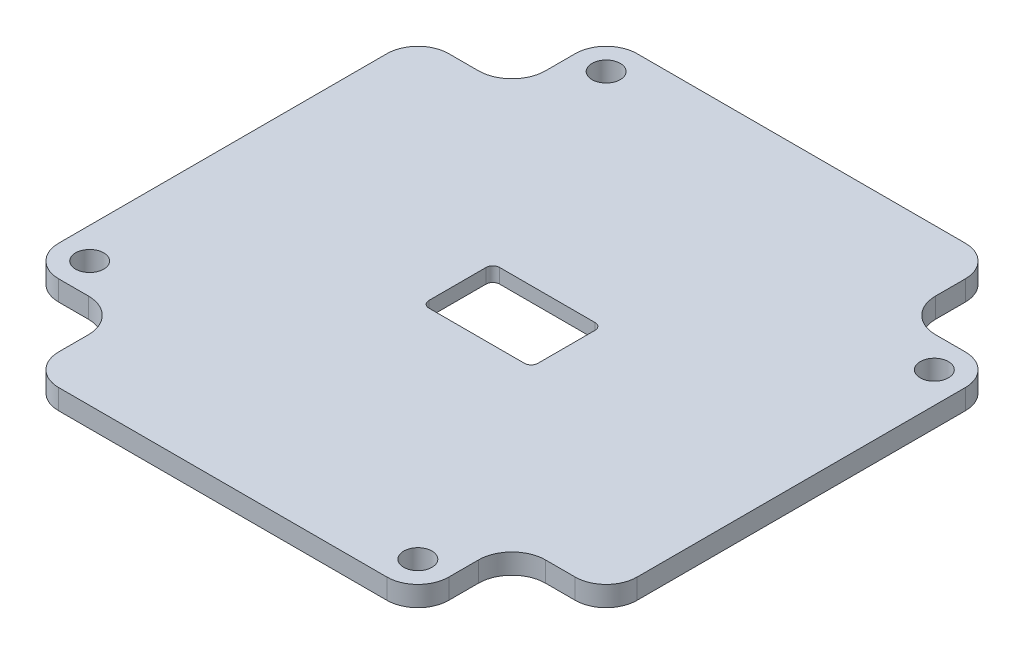
SolidWorks part; units mm, degrees
ref_plane "Front Plane" through (0, 0, 0) normal (0, 0, 1) x (1, 0, 0)
ref_plane "Top Plane" through (0, 0, 0) normal (0, 1, 0) x (1, 0, 0)
ref_plane "Right Plane" through (0, 0, 0) normal (1, 0, 0) x (0, 0, -1)
sketch "Sketch1" plane through (0, 0, 0) normal (0, 1, 0) x (1, 0, 0)
  line L1 (-43, -43) -> (43, -43)
  line L2 (-43, -43) -> (-43, 43)
  line L3 (-43, 43) -> (43, 43)
  line L4 (43, -43) -> (43, 43)
  line L5 (-43, -43) -> (43, 43) construction
  line L6 (-43, 43) -> (43, -43) construction
  point P0 (0, 0)
  dimension "D1" = 86
  dimension "D2" = 86
extrude "Boss-Extrude1" add sketch "Sketch1" along normal blind 3
sketch "Sketch2" plane through (0, 3, 0) normal (0, 1, 0) x (1, 0, 0)
  line L0 (29, 43) -> (29, 29)
  line L1 (-43, 43) -> (-29, 43)
  line L2 (-43, 43) -> (-43, 29)
  line L3 (-43, 29) -> (-29, 29)
  line L4 (-29, 43) -> (-29, 29)
  line L5 (29, 43) -> (43, 43)
  line L6 (43, 43) -> (43, 29)
  line L7 (29, 29) -> (43, 29)
  line L8 (29, -29) -> (29, -43)
  line L9 (29, -29) -> (43, -29)
  line L10 (43, -29) -> (43, -43)
  line L11 (29, -43) -> (43, -43)
  line L12 (-43, -29) -> (-43, -43)
  line L13 (-43, -29) -> (-29, -29)
  line L14 (-29, -29) -> (-29, -43)
  line L15 (-43, -43) -> (-29, -43)
  line L17 (-8.1, -5.25) -> (8.1, -5.25)
  line L18 (-8.1, -5.25) -> (-8.1, 5.25)
  line L19 (-8.1, 5.25) -> (8.1, 5.25)
  line L20 (8.1, -5.25) -> (8.1, 5.25)
  line L21 (-8.1, -5.25) -> (8.1, 5.25) construction
  line L22 (-8.1, 5.25) -> (8.1, -5.25) construction
  point P0 (0, 0)
  point P15 (0, 0)
  dimension "D1" = 16.2
  dimension "D2" = 14
  dimension "D3" = 14
  dimension "D6" = 10.5
  dimension "D4" = 2
  dimension "D5" = 2
extrude "Cut-Extrude1" cut sketch "Sketch2" against normal through all
fillet "Fillet1" radius 4.6 8 edges at (29, 1.5, 43) (-43, 1.5, -29) (-43, 1.5, 29) (-29, 1.5, 43) (43, 1.5, 29) (43, 1.5, -29) (29, 1.5, -43) (-29, 1.5, -43)
fillet "Fillet2" radius 5 4 edges at (29, 1.5, -29) (-29, 1.5, -29) (-29, 1.5, 29) (29, 1.5, 29)
sketch "Sketch3" plane through (0, 3, 0) normal (0, 1, 0) x (1, 0, 0)
  circle A1 centre (38.4, 24.4) radius 2.1
  circle A2 centre (-24.4, 38.4) radius 2.1
  circle A3 centre (24.4, -38.4) radius 2.1
  circle A4 centre (-38.4, -24.4) radius 2.1
  dimension "D1" = 4.2
  dimension "D2" = 4.2
  dimension "D3" = 4.2
  dimension "D4" = 4.2
extrude "Cut-Extrude2" cut sketch "Sketch3" against normal through all
sketch "Sketch4" plane through (0, 3, 0) normal (0, 1, 0) x (1, 0, 0)
  line L1 (11.75, -11.4) -> (-11.75, -11.4)
  line L2 (11.75, -11.4) -> (11.75, 11.4)
  line L3 (11.75, 11.4) -> (-11.75, 11.4)
  line L4 (-11.75, -11.4) -> (-11.75, 11.4)
  line L5 (11.75, -11.4) -> (-11.75, 11.4) construction
  line L6 (11.75, 11.4) -> (-11.75, -11.4) construction
  point P0 (0, 0)
  dimension "D1" = 23.5
  dimension "D2" = 22.8
extrude "Cut-Extrude3" cut sketch "Sketch4" along normal blind 0.85 from surface at -3 starting at face at (-24.4, 0, -36.3)
fillet "Fillet3" radius 3.4 4 edges at (-11.75, 0.425, 11.4) (11.75, 0.425, 11.4) (11.75, 0.425, -11.4) (-11.75, 0.425, -11.4)
sketch "Sketch5" plane through (0, 3, 0) normal (0, 1, 0) x (1, 0, 0)
  line L0 (11.75, -8) -> (11.75, 8) construction
  line L1 (-38, -11.4) -> (-16.75, -11.4)
  line L2 (-38, -11.4) -> (-38, 11.4)
  line L3 (-38, 11.4) -> (-16.75, 11.4)
  line L4 (-16.75, -11.4) -> (-16.75, 11.4)
  line L5 (-38, -11.4) -> (-16.75, 11.4) construction
  line L6 (-38, 11.4) -> (-16.75, -11.4) construction
  line L7 (-11.75, 16.4) -> (11.75, 16.4)
  line L8 (-11.75, 16.4) -> (-11.75, 38)
  line L9 (-11.75, 38) -> (11.75, 38)
  line L10 (11.75, 16.4) -> (11.75, 38)
  line L11 (-11.75, 16.4) -> (11.75, 38) construction
  line L12 (-11.75, 38) -> (11.75, 16.4) construction
  line L13 (16.75, -11.4) -> (38, -11.4)
  line L14 (16.75, -11.4) -> (16.75, 11.4)
  line L15 (16.75, 11.4) -> (38, 11.4)
  line L16 (38, -11.4) -> (38, 11.4)
  line L17 (16.75, -11.4) -> (38, 11.4) construction
  line L18 (16.75, 11.4) -> (38, -11.4) construction
  line L19 (-11.75, -16.4) -> (11.75, -16.4)
  line L20 (-11.75, -16.4) -> (-11.75, -38)
  line L21 (-11.75, -38) -> (11.75, -38)
  line L22 (11.75, -16.4) -> (11.75, -38)
  line L23 (-11.75, -16.4) -> (11.75, -38) construction
  line L24 (-11.75, -38) -> (11.75, -16.4) construction
  line L25 (8.35, 11.4) -> (-8.35, 11.4) construction
  line L26 (-43, 24.4) -> (-43, -24.4) construction
  line L27 (-11.75, 8) -> (-11.75, -8) construction
  line L28 (43, -24.4) -> (43, 24.4) construction
  line L29 (8.35, 11.4) -> (-8.35, 11.4) construction
  line L30 (24.4, 43) -> (-24.4, 43) construction
  line L31 (-8.35, -11.4) -> (8.35, -11.4) construction
  line L32 (-24.4, -43) -> (24.4, -43) construction
  line L33 (-24, 43) -> (-24, -43)
  line L34 (-38, 38) -> (-16.75, 38)
  line L35 (-38, 38) -> (-38, 16.4)
  line L36 (-38, 16.4) -> (-16.75, 16.4)
  line L37 (-16.75, 38) -> (-16.75, 16.4)
  line L38 (-38, 38) -> (-16.75, 16.4) construction
  line L39 (-38, 16.4) -> (-16.75, 38) construction
  line L40 (-38, -38) -> (-16.75, -38)
  line L41 (-38, -38) -> (-38, -16.4)
  line L42 (-38, -16.4) -> (-16.75, -16.4)
  line L43 (-16.75, -38) -> (-16.75, -16.4)
  line L44 (-38, -38) -> (-16.75, -16.4) construction
  line L45 (-38, -16.4) -> (-16.75, -38) construction
  line L46 (38, -38) -> (16.75, -38)
  line L47 (38, -38) -> (38, -16.4)
  line L48 (38, -16.4) -> (16.75, -16.4)
  line L49 (16.75, -38) -> (16.75, -16.4)
  line L50 (38, -38) -> (16.75, -16.4) construction
  line L51 (38, -16.4) -> (16.75, -38) construction
  line L52 (38, 16.4) -> (16.75, 16.4)
  line L53 (38, 16.4) -> (38, 38)
  line L54 (38, 38) -> (16.75, 38)
  line L55 (16.75, 16.4) -> (16.75, 38)
  line L56 (38, 16.4) -> (16.75, 38) construction
  line L57 (38, 38) -> (16.75, 16.4) construction
  line L58 (24, 43) -> (24, -43)
  line L59 (43, -24) -> (-43, -24)
  line L60 (-43, 24) -> (43, 24)
  line L61 (-29, 34) -> (-29, 38.4) construction
  line L62 (-38.4, 29) -> (-34, 29) construction
  line L63 (29, 38.4) -> (29, 34) construction
  line L64 (38.4, -29) -> (34, -29) construction
  circle A0 centre (-24.4, 38.4) radius 7.1
  circle A1 centre (38.4, 24.4) radius 7.1
  circle A2 centre (24.4, -38.4) radius 7.1
  circle A3 centre (-38.4, -24.4) radius 7.1
  circle A8 centre (-24.4, 38.4) radius 2.1 construction
  circle A11 centre (38.4, 24.4) radius 2.1 construction
  circle A16 centre (24.4, -38.4) radius 2.1 construction
  circle A18 centre (-38.4, -24.4) radius 2.1 construction
  circle A20 centre (34, 34) radius 10
  circle A21 centre (-34, 34) radius 10
  circle A22 centre (-34, -34) radius 10
  circle A23 centre (34, -34) radius 10
  point P0 (-27.375, 0)
  point P5 (0, 27.2)
  point P10 (27.375, 0)
  point P15 (0, -27.2)
  point P20 (-27.375, -27.2)
  point P41 (-27.375, 27.2)
  point P49 (27.375, -27.2)
  point P54 (27.375, 27.2)
  dimension "D9" = 5
  dimension "D10" = 5
  dimension "D11" = 5
  dimension "D12" = 5
  dimension "D1" = 5
  dimension "D2" = 5
  dimension "D3" = 5
  dimension "D4" = 5
  dimension "D5" = 5
  dimension "D6" = 5
  dimension "D7" = 5
  dimension "D8" = 5
  dimension "D13" = 5
  dimension "D14" = 5
  dimension "D15" = 5
  dimension "D16" = 5
extrude "Cut-Extrude4" cut sketch "Sketch5" against normal through all from offset 1.5 contours L8 L60 L10 L9 | L60 L8 L7 L10 | L33 L3 L2 L1 | L3 L33 L1 L4 | L15 L58 L13 L16 | L58 L15 L14 L13 | L59 L22 L19 L20 | L22 L59 L20 L21 | L59 L58 L48 L49 | L59 L47 L48 L58 | A2 L58 L59 L49 L46 | A23 L59 L58 A2 | L43 L59 L33 L40 | L59 L43 L42 L33 | A3 L59 L33 L42 L41 | A22 L33 L59 A3 | L60 L35 L36 L33 | A0 L33 L60 L37 L34 | L60 L33 L36 L37 | A21 L60 L33 A0 | L55 L60 L58 L54 | L60 L55 L52 L58 | A1 L60 L58 L52 L53 | A20 L58 L60 A1 offset against normal yes
fillet "Fillet4" radius 3 27 edges at (-16.75, 0.75, -11.4) (-38, 0.75, -11.4) (-16.75, 0.75, 11.4) (-38, 0.75, 11.4) (-24, 0.75, 38) (-16.75, 0.75, 38) (-16.75, 0.75, 16.4) (-11.75, 0.75, 38) (11.75, 0.75, 38) (11.75, 0.75, 16.4) (-11.75, 0.75, 16.4) (38, 0.75, 16.4) (16.75, 0.75, 16.4) (38, 0.75, 11.4) (16.75, 0.75, 11.4) (16.75, 0.75, -11.4) (38, 0.75, -11.4) (-38, 0.75, -24) (-38, 0.75, -16.4) (24, 0.75, -38) (16.75, 0.75, -38) (11.75, 0.75, -38) (-11.75, 0.75, -38) (16.75, 0.75, -16.4) (11.75, 0.75, -16.4) (-11.75, 0.75, -16.4) (-16.75, 0.75, -16.4)
fillet "Fillet5" radius 1 4 edges at (-8.1, 1.925, 5.25) (8.1, 1.925, 5.25) (8.1, 1.925, -5.25) (-8.1, 1.925, -5.25)
